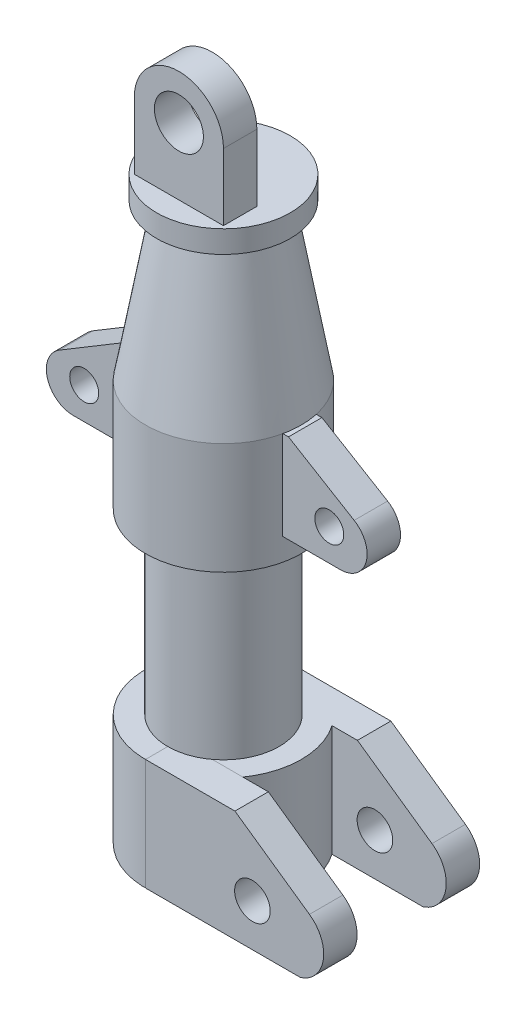
SolidWorks part; units mm, degrees
ref_plane "Front Plane" through (0, 0, 0) normal (0, 0, 1) x (1, 0, 0)
ref_plane "Top Plane" through (0, 0, 0) normal (0, 1, 0) x (1, 0, 0)
ref_plane "Right Plane" through (0, 0, 0) normal (1, 0, 0) x (0, 0, -1)
sketch "Sketch3" plane through (0, 0, 0) normal (0, 0, 1) x (1, 0, 0)
  line L0 (0, 0) -> (0, 260) construction
  line L1 (0, 260) -> (30, 260)
  line L2 (30, 260) -> (30, 250)
  line L3 (30, 250) -> (22.6571, 250)
  line L4 (22.6571, 250) -> (35, 180)
  line L5 (35, 180) -> (35, 130)
  line L6 (35, 130) -> (25, 130)
  line L7 (0, 0) -> (0, 260)
  line L8 (25, 130) -> (25, 50)
  line L9 (25, 50) -> (35, 50)
  line L10 (35, 50) -> (35, 0)
  line L11 (35, 0) -> (0, 0)
  dimension "D1" = 30
  dimension "D2" = 10
  dimension "D3" = 10
  dimension "D4" = 35
  dimension "D5" = 260
  dimension "D6" = 50
  dimension "D7" = 80
  dimension "D8" = 25
  dimension "D9" = 35
revolve "Revolve1" add sketch "Sketch3" angle 360 about L0
ref_plane "Plane1" through (0, 0, 5) normal (0, 0, 1) x (1, 0, 0)
sketch "Sketch4" plane through (0, 0, 5) normal (0, 0, 1) x (1, 0, 0)
  line L0 (-20, 260) -> (-20, 290)
  line L1 (30, 260) -> (-30, 260) construction
  line L3 (20, 290) -> (20, 260)
  line L4 (20, 260) -> (-20, 260)
  arc A0 (20, 290) -> (-20, 290) centre (0, 290) ccw
  circle A1 centre (0, 290) radius 11
  dimension "D3" = 22
  dimension "D1" = 30
  dimension "D2" = 40
extrude "Boss-Extrude2" add sketch "Sketch4" along normal blind 15
sketch "Sketch5" plane through (0, 0, 0) normal (0, 0, 1) x (1, 0, 0)
  line L0 (35, 180) -> (36.6994, 180)
  line L1 (36.6994, 180) -> (66.1805, 162.286)
  line L3 (60, 140) -> (35, 140)
  line L4 (35, 130) -> (35, 180) construction
  line L6 (0, 0) -> (0, 231.3678) construction
  line L7 (-35, 0) -> (35, 0) construction
  line L8 (60, 140) -> (60, 152) construction
  line L9 (35, 180) -> (32.7718, 180)
  line L10 (-60, 140) -> (-35, 140)
  line L11 (60, 158.4433) -> (60, 177.216) construction
  line L12 (35, 180) -> (-35, 180) construction
  line L13 (32.7718, 180) -> (32.7718, 140)
  line L14 (32.7718, 140) -> (35, 140)
  line L15 (-35, 180) -> (-36.6994, 180)
  line L16 (-35, 180) -> (-32.7718, 180)
  line L17 (-32.7718, 140) -> (-35, 140)
  line L18 (-32.7718, 180) -> (-32.7718, 140)
  line L19 (-36.6994, 180) -> (-66.1805, 162.286)
  circle A0 centre (55, 154.29) radius 6.5
  arc A1 (60, 140) -> (66.1805, 162.286) centre (60, 152) ccw
  circle A2 centre (-55, 154.29) radius 6.5
  arc A3 (-60, 140) -> (-66.1805, 162.286) centre (-60, 152) cw
  dimension "D2" = 13
  dimension "D8" = 24
  dimension "D1" = 140
  dimension "D3" = 31
  dimension "D4" = 14.29
  dimension "D5" = 55
  dimension "D7" = 60
extrude "Boss-Extrude3" add sketch "Sketch5" along normal mid plane 15 separate body
ref_plane "Plane2" through (0, 0, 35) normal (0, 0, 1) x (1, 0, 0)
sketch "Sketch8" plane through (0, 0, 35) normal (0, 0, 1) x (1, 0, 0)
  line L0 (35, 50) -> (40.1525, 50)
  line L2 (69.5603, 0) -> (35, 0)
  line L3 (35, 0) -> (35, 50) construction
  line L4 (0, 0) -> (0, 103.9278) construction
  line L5 (65, 14.29) -> (65, -4.8693) construction
  line L6 (60.3478, 14.29) -> (65, 14.29) construction
  line L7 (35, 50) -> (0, 50)
  line L8 (40.1525, 50) -> (73.6036, 26.5773)
  line L9 (35, 50) -> (-35, 50) construction
  line L10 (0, 50) -> (0, 0)
  line L11 (0, 0) -> (35, 0)
  circle A0 centre (48, 19) radius 8
  arc A2 (69.5603, 0) -> (73.6036, 26.5773) centre (65, 14.29) ccw
  dimension "D6" = 16
  dimension "D1" = 19
  dimension "D2" = 48
  dimension "D3" = 35
  dimension "D4" = 17
  dimension "D5" = 14.29
extrude "Boss-Extrude4" add sketch "Sketch8" against normal blind 15 separate body
ref_plane "Plane3" through (0, 0, -35) normal (0, 0, 1) x (1, 0, 0)
sketch "Sketch10" plane through (0, 0, -35) normal (0, 0, 1) x (1, 0, 0)
  line L0 (0, 0) -> (0, 50)
  line L1 (35, 50) -> (-35, 50) construction
  line L2 (0, 50) -> (40.1525, 50)
  line L3 (40.1525, 50) -> (73.6036, 26.5773)
  line L4 (69.5603, 0) -> (0, 0)
  circle A0 centre (48, 19) radius 8
  arc A1 (69.5603, 0) -> (73.6036, 26.5773) centre (65, 14.29) ccw construction
  spline S0 degree 3 poles (73.6036, 26.5773) (75.1271, 25.5135) (76.9804, 23.6124) (78.7313, 20.5056) (79.7261, 17.7252) (80.1117, 14.6311) (79.8073, 11.2472) (78.8824, 8.3037) (77.3611, 5.6512) (74.6727, 2.458) (71.8146, 0.7129) (69.5603, 0) knots 0 0 0 0 0.167351 0.234882 0.32047 0.43212 0.512919 0.625495 0.707153 0.787292 1 1 1 1
extrude "Boss-Extrude5" add sketch "Sketch10" along normal blind 15
sketch "Sketch11" plane through (0, 0, 0) normal (0, -1, 0) x (1, 0, 0)
  circle A0 centre (0, 0) radius 20
  dimension "D1" = 40
extrude "Cut-Extrude1" cut sketch "Sketch11" against normal blind 235
